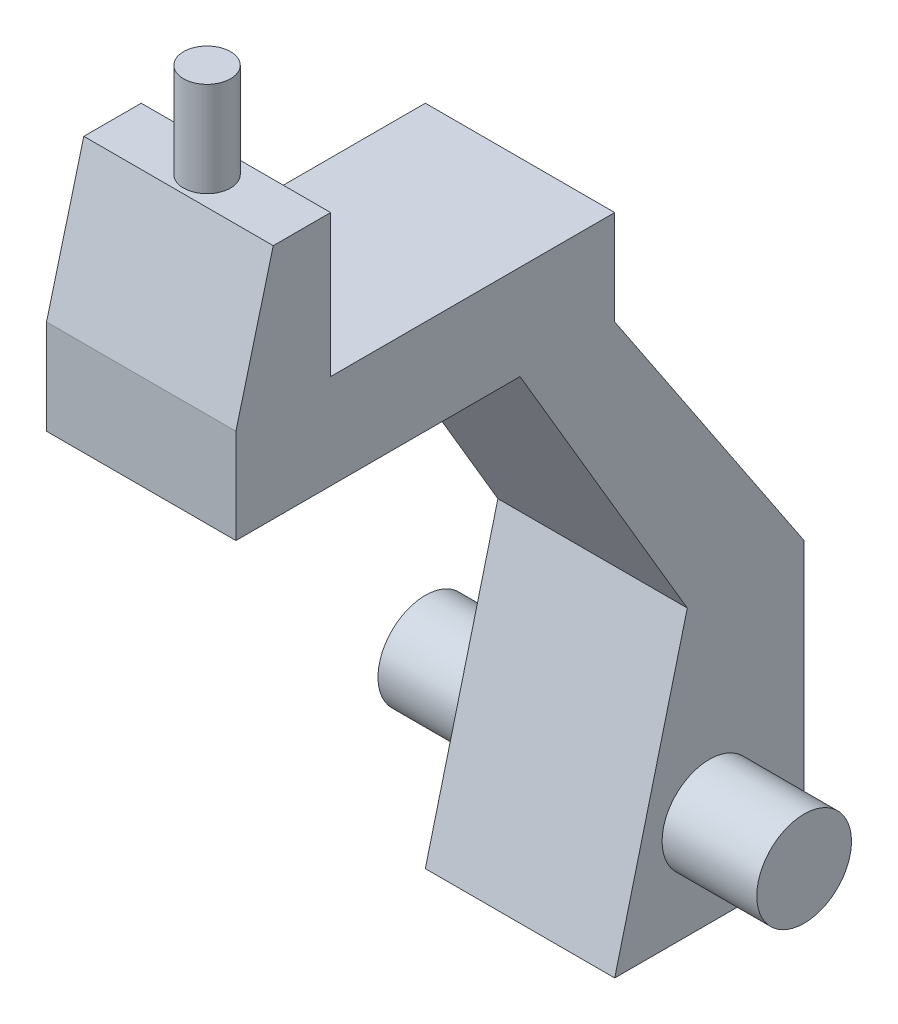
SolidWorks part; units mm, degrees
ref_plane "Front Plane" through (0, 0, 0) normal (0, 0, 1) x (1, 0, 0)
ref_plane "Top Plane" through (0, 0, 0) normal (0, 1, 0) x (1, 0, 0)
ref_plane "Right Plane" through (0, 0, 0) normal (1, 0, 0) x (0, 0, -1)
sketch "Sketch1" plane through (0, 0, 0) normal (0, 1, 0) x (1, 0, 0)
  line L1 (-8.1119, 8.4615) -> (11.8881, 8.4615)
  line L2 (-8.1119, 8.4615) -> (-8.1119, -11.5385)
  line L3 (-8.1119, -11.5385) -> (11.8881, -11.5385)
  line L4 (11.8881, 8.4615) -> (11.8881, -11.5385)
  dimension "D1" = 20
  dimension "D2" = 20
extrude "Boss-Extrude2" add sketch "Sketch1" along normal blind 30
sketch "Sketch2" plane through (11.8881, 0, 0) normal (1, 0, 0) x (0, 0, -1)
  line L0 (-11.5385, 0) -> (8.4615, 0) construction
  line L1 (8.4615, 30) -> (8.4615, 0) construction
  circle A0 centre (-1.5385, 10) radius 5
  dimension "D1" = 10
  dimension "D2" = 10
extrude "Boss-Extrude3" add sketch "Sketch2" along normal blind 10
ref_plane "Middle Plane" through (1.8881, 0, 0) normal (1, 0, 0) x (0, 0, -1)
mirror "Mirror1" about plane through (1.8881, 0, 0) normal (1, 0, 0) of "Boss-Extrude3"
sketch "Sketch3" plane through (11.8881, 0, 0) normal (1, 0, 0) x (0, 0, -1)
  line L0 (-11.5385, 0) -> (-3.8757, 30)
  line L1 (-11.5385, 30) -> (8.4615, 30) construction
  line L2 (-3.8757, 30) -> (-11.5385, 30)
  line L3 (-11.5385, 30) -> (-11.5385, 0)
extrude "Cut-Extrude2" cut sketch "Sketch3" against normal blind 20
sketch "Sketch5" plane through (0, 30, 0) normal (0, 1, 0) x (1, 0, 0)
  line L1 (-8.1119, 8.4615) -> (11.8881, 8.4615)
  line L2 (-8.1119, 8.4615) -> (-8.1119, -21.5385)
  line L3 (-8.1119, -21.5385) -> (11.8881, -21.5385)
  line L4 (11.8881, 8.4615) -> (11.8881, -21.5385)
  dimension "D1" = 20
  dimension "D2" = 30
extrude "Boss-Extrude4" add sketch "Sketch5" along normal blind 30
sketch "Sketch6" plane through (11.8881, 0, 0) normal (1, 0, 0) x (0, 0, -1)
  line L0 (-3.8757, 30) -> (-21.5385, 60)
  line L1 (-21.5385, 60) -> (-21.5385, 30)
  line L2 (-21.5385, 30) -> (-3.8757, 30)
  line L3 (8.4615, 30) -> (8.4615, 60)
  line L4 (8.4615, 60) -> (8.4615, 0) construction
  line L5 (8.4615, 60) -> (-11.5385, 60)
  line L6 (-21.5385, 60) -> (8.4615, 60) construction
  line L7 (-11.5385, 60) -> (8.4615, 30)
  dimension "D1" = 20
extrude "Cut-Extrude3" cut sketch "Sketch6" against normal blind 20
sketch "Sketch7" plane through (0, 60, 0) normal (0, 1, 0) x (1, 0, 0)
  line L1 (-8.1119, -11.5385) -> (11.8881, -11.5385)
  line L2 (-8.1119, -11.5385) -> (-8.1119, -51.5385)
  line L3 (-8.1119, -51.5385) -> (11.8881, -51.5385)
  line L4 (11.8881, -11.5385) -> (11.8881, -51.5385)
  dimension "D1" = 20
  dimension "D2" = 40
extrude "Boss-Extrude5" add sketch "Sketch7" along normal blind 10
sketch "Sketch8" plane through (0, 70, 0) normal (0, 1, 0) x (1, 0, 0)
  line L0 (11.8881, -51.5385) -> (11.8881, -11.5385) construction
  line L1 (-8.1119, -51.5385) -> (11.8881, -51.5385)
  line L2 (-8.1119, -51.5385) -> (-8.1119, -41.5385)
  line L3 (-8.1119, -41.5385) -> (11.8881, -41.5385)
  line L4 (11.8881, -51.5385) -> (11.8881, -41.5385)
  dimension "D1" = 10
extrude "Boss-Extrude6" add sketch "Sketch8" along normal blind 15
sketch "Sketch9" plane through (11.8881, 0, 0) normal (1, 0, 0) x (0, 0, -1)
  line L0 (-51.5385, 70) -> (-47.5985, 85)
  line L1 (-51.5385, 85) -> (-51.5385, 60) construction
  line L2 (-51.5385, 85) -> (-41.5385, 85) construction
  line L3 (-47.5985, 85) -> (-51.5385, 85)
  line L4 (-51.5385, 85) -> (-51.5385, 70)
extrude "Cut-Extrude4" cut sketch "Sketch9" against normal blind 20
sketch "Sketch10" plane through (0, 85, 0) normal (0, 1, 0) x (1, 0, 0)
  line L0 (1.8881, -33) -> (1.8881, 33) construction
  line L3 (11.8881, -41.5385) -> (-8.1119, -41.5385) construction
  circle A1 centre (1.8881, -44.5885) radius 2.4816
  dimension "D1" = 3.05
extrude "Boss-Extrude7" add sketch "Sketch10" along normal blind 10
